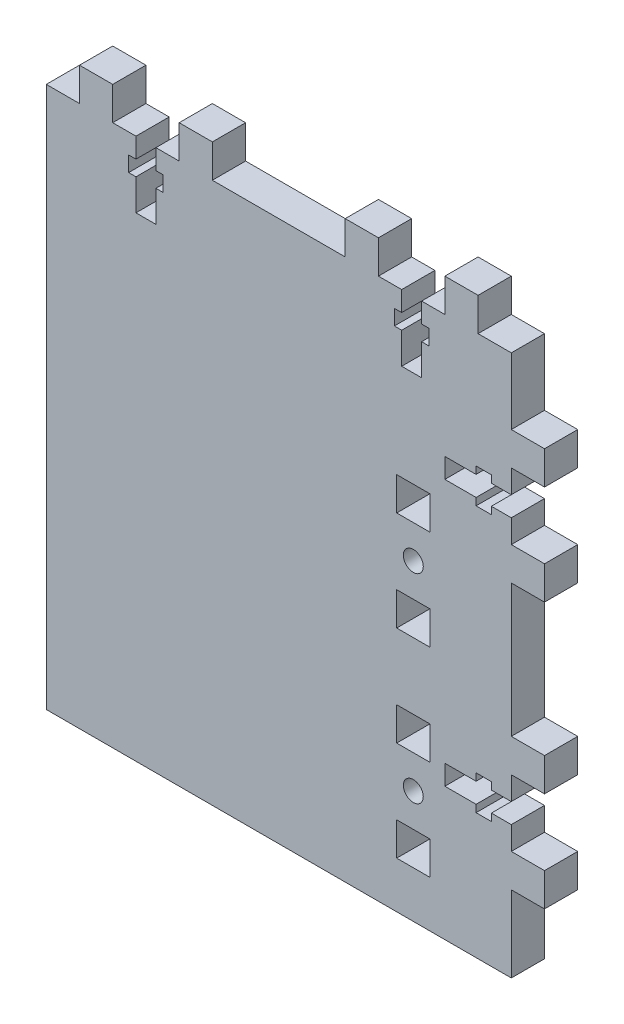
SolidWorks part; units mm, degrees
ref_plane "Front Plane" through (0, 0, 0) normal (0, 0, 1) x (1, 0, 0)
ref_plane "Top Plane" through (0, 0, 0) normal (0, 1, 0) x (1, 0, 0)
ref_plane "Right Plane" through (0, 0, 0) normal (1, 0, 0) x (0, 0, -1)
sketch "Sketch1" plane through (0, 0, 0) normal (0, 0, 1) x (1, 0, 0)
  line L0 (70, 81.5) -> (70, 71.5)
  line L1 (0, 0) -> (70, 0) construction
  line L2 (0, 0) -> (0, 81.5)
  line L3 (0, 81.5) -> (70, 81.5) construction
  line L4 (70, 0) -> (70, 81.5) construction
  line L5 (70, 51.5) -> (70, 31.5)
  line L6 (70, 11.5) -> (70, 0)
  line L7 (70, 61.5) -> (58.7792, 61.5) construction
  line L8 (70, 60) -> (70, 56.5)
  line L9 (75, 56.5) -> (75, 51.5)
  line L10 (75, 51.5) -> (70, 51.5)
  line L11 (75, 56.5) -> (70, 56.5)
  line L12 (70, 63) -> (70, 66.5)
  line L13 (70, 66.5) -> (75, 66.5)
  line L14 (75, 66.5) -> (75, 71.5)
  line L15 (75, 71.5) -> (70, 71.5)
  line L16 (70, 21.5) -> (58.7792, 21.5) construction
  line L17 (70, 20) -> (70, 16.5)
  line L18 (75, 16.5) -> (75, 11.5)
  line L19 (75, 11.5) -> (70, 11.5)
  line L20 (75, 16.5) -> (70, 16.5)
  line L21 (70, 23) -> (70, 26.5)
  line L22 (70, 26.5) -> (75, 26.5)
  line L23 (75, 26.5) -> (75, 31.5)
  line L24 (75, 31.5) -> (70, 31.5)
  line L25 (70, 60) -> (70, 63) construction
  line L26 (70, 63) -> (67, 63)
  line L27 (64.7, 63) -> (64.7, 64.1)
  line L28 (67, 58.9) -> (64.7, 58.9)
  line L29 (67, 64.1) -> (67, 63)
  line L30 (64.7, 63) -> (60, 63)
  line L31 (60, 63) -> (60, 60)
  line L32 (60, 60) -> (64.7, 60)
  line L33 (67, 60) -> (67, 58.9)
  line L34 (64.7, 64.1) -> (67, 64.1)
  line L35 (64.7, 58.9) -> (64.7, 60)
  line L36 (67, 60) -> (70, 60)
  line L37 (60, 61.5) -> (70, 61.5) construction
  line L38 (70, 20) -> (70, 23) construction
  line L39 (70, 23) -> (67, 23)
  line L40 (64.7, 23) -> (64.7, 24.1)
  line L41 (67, 18.9) -> (64.7, 18.9)
  line L42 (67, 24.1) -> (67, 23)
  line L43 (64.7, 23) -> (60, 23)
  line L44 (60, 23) -> (60, 20)
  line L45 (60, 20) -> (64.7, 20)
  line L46 (67, 20) -> (67, 18.9)
  line L47 (64.7, 24.1) -> (67, 24.1)
  line L48 (64.7, 18.9) -> (64.7, 20)
  line L49 (67, 20) -> (70, 20)
  line L50 (60, 21.5) -> (70, 21.5) construction
  line L51 (57.75, 94.8027) -> (57.75, 0) construction
  line L52 (0, 81.5) -> (5, 81.5)
  line L53 (25, 81.5) -> (45, 81.5)
  line L54 (65, 81.5) -> (70, 81.5)
  line L55 (15, 81.5) -> (15, 83.582) construction
  line L56 (16.5, 81.5) -> (20, 81.5)
  line L57 (20, 86.5) -> (25, 86.5)
  line L58 (25, 86.5) -> (25, 81.5)
  line L59 (20, 86.5) -> (20, 81.5)
  line L60 (13.5, 81.5) -> (10, 81.5)
  line L61 (10, 81.5) -> (10, 86.5)
  line L62 (10, 86.5) -> (5, 86.5)
  line L63 (5, 86.5) -> (5, 81.5)
  line L64 (16.5, 81.5) -> (13.5, 81.5) construction
  line L65 (13.5, 81.5) -> (13.5, 78.5)
  line L66 (13.5, 76.2) -> (12.4, 76.2)
  line L67 (17.6, 78.5) -> (17.6, 76.2)
  line L68 (12.4, 78.5) -> (13.5, 78.5)
  line L69 (13.5, 76.2) -> (13.5, 71.5)
  line L70 (13.5, 71.5) -> (16.5, 71.5)
  line L71 (16.5, 71.5) -> (16.5, 76.2)
  line L72 (16.5, 78.5) -> (17.6, 78.5)
  line L73 (12.4, 76.2) -> (12.4, 78.5)
  line L74 (17.6, 76.2) -> (16.5, 76.2)
  line L75 (16.5, 78.5) -> (16.5, 81.5)
  line L76 (15, 71.5) -> (15, 81.5) construction
  line L77 (55, 81.5) -> (55, 83.582) construction
  line L78 (56.5, 81.5) -> (60, 81.5)
  line L79 (60, 86.5) -> (65, 86.5)
  line L80 (65, 86.5) -> (65, 81.5)
  line L81 (60, 86.5) -> (60, 81.5)
  line L82 (53.5, 81.5) -> (50, 81.5)
  line L83 (50, 81.5) -> (50, 86.5)
  line L84 (50, 86.5) -> (45, 86.5)
  line L85 (45, 86.5) -> (45, 81.5)
  line L86 (56.5, 81.5) -> (53.5, 81.5) construction
  line L87 (53.5, 81.5) -> (53.5, 78.5)
  line L88 (53.5, 76.2) -> (52.4, 76.2)
  line L89 (57.6, 78.5) -> (57.6, 76.2)
  line L90 (52.4, 78.5) -> (53.5, 78.5)
  line L91 (53.5, 76.2) -> (53.5, 71.5)
  line L92 (53.5, 71.5) -> (56.5, 71.5)
  line L93 (56.5, 71.5) -> (56.5, 76.2)
  line L94 (56.5, 78.5) -> (57.6, 78.5)
  line L95 (52.4, 76.2) -> (52.4, 78.5)
  line L96 (57.6, 76.2) -> (56.5, 76.2)
  line L97 (56.5, 78.5) -> (56.5, 81.5)
  line L98 (55, 71.5) -> (55, 81.5) construction
  line L102 (0, 0) -> (70, 0)
  point P11 (72.5, 31.5)
  point P62 (65, 84)
  point P90 (0, 0)
  line B0 (52.75, 42) -> (52.75, 37)
  line B1 (52.75, 42) -> (57.75, 42)
  line B2 (57.75, 42) -> (57.75, 37)
  line B3 (52.75, 37) -> (57.75, 37)
  line B4 (52.75, 52) -> (52.75, 57)
  line B5 (52.75, 52) -> (57.75, 52)
  line B6 (57.75, 52) -> (57.75, 57)
  line B7 (52.75, 57) -> (57.75, 57)
  circle B8 centre (55.25, 47) radius 1.5
  line B9 (52.75, 12) -> (52.75, 7)
  line B10 (52.75, 12) -> (57.75, 12)
  line B11 (57.75, 12) -> (57.75, 7)
  line B12 (52.75, 7) -> (57.75, 7)
  line B13 (52.75, 22) -> (52.75, 27)
  line B14 (52.75, 22) -> (57.75, 22)
  line B15 (57.75, 22) -> (57.75, 27)
  line B16 (52.75, 27) -> (57.75, 27)
  circle B17 centre (55.25, 17) radius 1.5
  dimension "D1" = 10
  dimension "D2" = 20
  dimension "D3" = 70
  dimension "D5" = 10
  dimension "D6" = 5
  dimension "D7" = 5
  dimension "D8" = 10
  dimension "D9" = 5
  dimension "D10" = 5
  dimension "D11" = 5.2
  dimension "D12" = 3
  dimension "D13" = 2.3
  dimension "D14" = 3
  dimension "D15" = 10
  dimension "D16" = 5.2
  dimension "D17" = 3
  dimension "D18" = 2.3
  dimension "D19" = 3
  dimension "D20" = 10
  dimension "D21" = 12.25
  dimension "D22" = 24.5
  dimension "D23" = 10
  dimension "D24" = 5
  dimension "D25" = 20
  dimension "D26" = 10
  dimension "D27" = 5
  dimension "D28" = 5
  dimension "D29" = 5.2
  dimension "D30" = 3
  dimension "D31" = 2.3
  dimension "D32" = 3
  dimension "D33" = 10
  dimension "D34" = 10
  dimension "D35" = 5
  dimension "D36" = 5
  dimension "D37" = 5.2
  dimension "D38" = 3
  dimension "D39" = 2.3
  dimension "D40" = 3
  dimension "D41" = 10
  dimension "D42" = 7
sketch_block_instance "Trou M3 plots 5mm-1"
sketch_block "Trou M3 plots 5mm" parameters "D2"=3, "D1"=5, "D3"=5, "D4"=10
sketch_block_instance "Trou M3 plots 5mm-2"
extrude "Boss-Extrude1" add sketch "Sketch1" along normal blind 5
